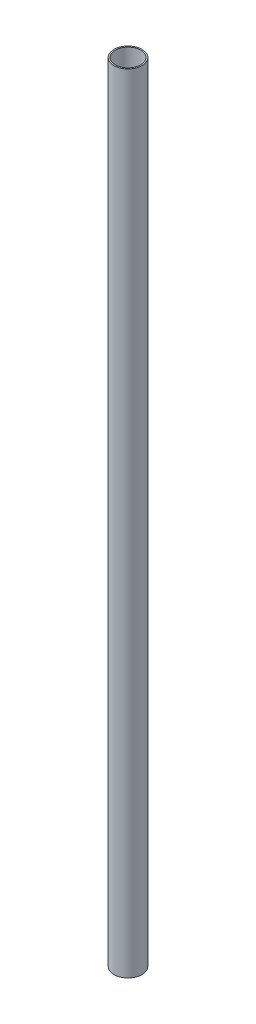
SolidWorks part; units mm, degrees
ref_plane "Front Plane" through (0, 0, 0) normal (0, 0, 1) x (1, 0, 0)
ref_plane "Top Plane" through (0, 0, 0) normal (0, 1, 0) x (1, 0, 0)
ref_plane "Right Plane" through (0, 0, 0) normal (1, 0, 0) x (0, 0, -1)
sketch "Sketch1" plane through (0, 0, 0) normal (0, 1, 0) x (1, 0, 0)
  circle A0 centre (0, 0) radius 9.525
  dimension "D1" = 19.05
extrude "Extrude1" add sketch "Sketch1" along normal blind 533.4
sketch "Sketch2" plane through (0, 0, 0) normal (0, 1, 0) x (1, 0, 0)
  circle A0 centre (0, 0) radius 8.636
  dimension "D1" = 17.272
extrude "Cut-Extrude1" cut sketch "Sketch2" along normal blind 1016
